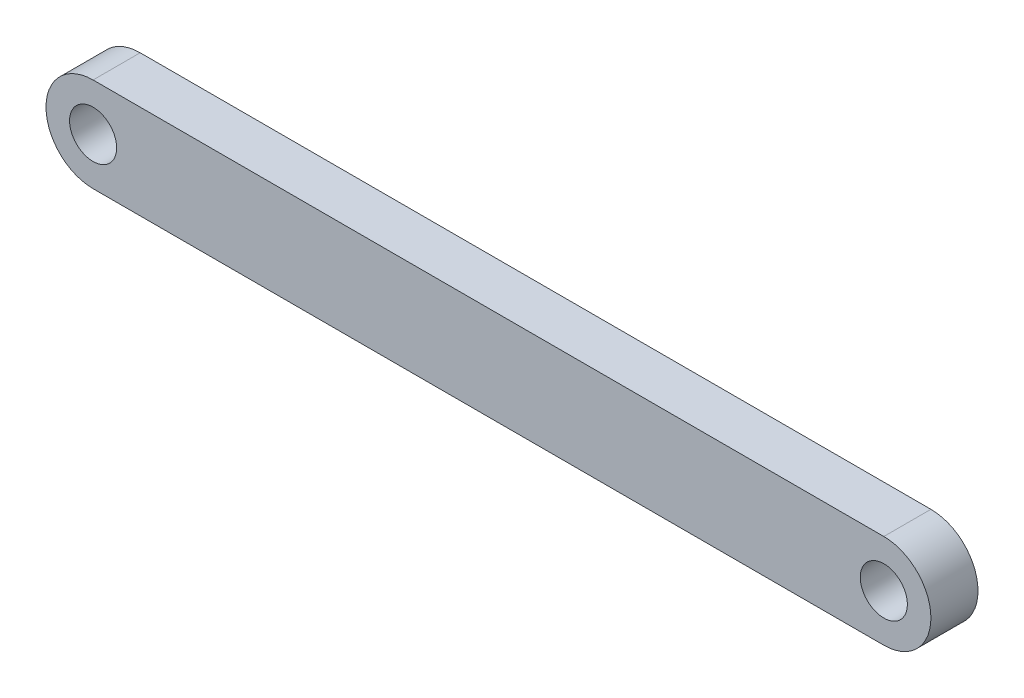
SolidWorks part; units mm, degrees
ref_plane "Plano frontal" through (0, 0, 0) normal (0, 0, 1) x (1, 0, 0)
ref_plane "Plano superior" through (0, 0, 0) normal (0, 1, 0) x (1, 0, 0)
ref_plane "Plano direito" through (0, 0, 0) normal (1, 0, 0) x (0, 0, -1)
sketch "Esboço1" plane through (0, 0, 0) normal (0, 0, 1) x (1, 0, 0)
  line L0 (-41.98, 5) -> (41.98, 5)
  line L1 (-41.98, 0) -> (41.98, 0) construction
  line L2 (-41.98, -5) -> (41.98, -5)
  arc A0 (-41.98, 5) -> (-41.98, -5) centre (-41.98, 0) ccw
  arc A1 (41.98, 5) -> (41.98, -5) centre (41.98, 0) cw
  circle A2 centre (-41.98, 0) radius 2.5
  circle A3 centre (41.98, 0) radius 2.5
  point P3 (0, 5)
  dimension "D1" = 83.96
  dimension "D2" = 5
extrude "Ressalto-extrusão1" add sketch "Esboço1" along normal blind 5
